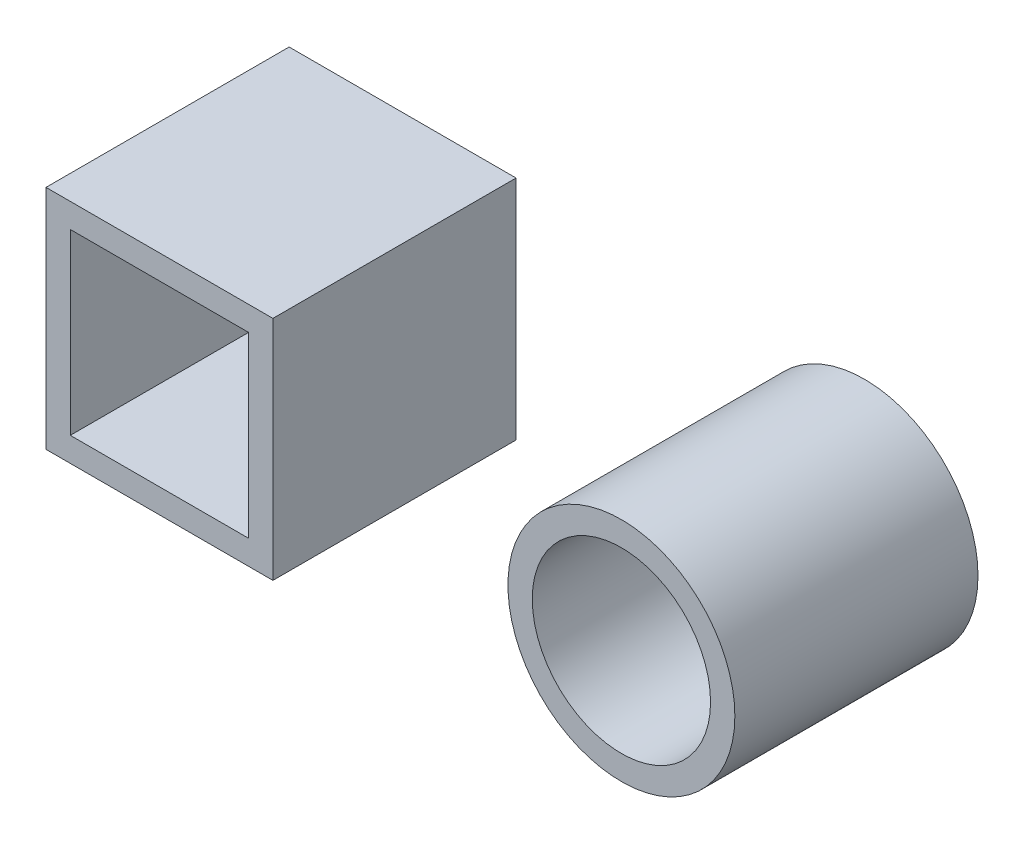
SolidWorks part; units mm, degrees
ref_plane "Front Plane" through (0, 0, 0) normal (0, 0, 1) x (1, 0, 0)
ref_plane "Top Plane" through (0, 0, 0) normal (0, 1, 0) x (1, 0, 0)
ref_plane "Right Plane" through (0, 0, 0) normal (1, 0, 0) x (0, 0, -1)
sketch "Sketch3" plane through (0, 0, 0) normal (0, 0, 1) x (1, 0, 0)
  line L0 (-122.5, 0) -> (122.5, 0) construction
  line L1 (-122.5, 60) -> (122.5, 60)
  line L2 (-122.5, 60) -> (-122.5, -60)
  line L3 (-122.5, -60) -> (122.5, -60)
  line L4 (122.5, 60) -> (122.5, -60)
  line L5 (0, 60) -> (0, -60) construction
  line L6 (-22.5, -12.9904) -> (0, 25.9808)
  line L7 (-92.5, 22.5) -> (-47.5, 22.5)
  line L8 (-92.5, 22.5) -> (-92.5, -22.5)
  line L9 (-92.5, -22.5) -> (-47.5, -22.5)
  line L10 (-47.5, 22.5) -> (-47.5, -22.5)
  line L11 (-92.5, 22.5) -> (-47.5, -22.5) construction
  line L12 (-92.5, -22.5) -> (-47.5, 22.5) construction
  line L14 (-1.3522, 0) -> (0, -1.3522)
  line L18 (0, 25.9808) -> (22.5, -12.9904)
  line L19 (22.5, -12.9904) -> (-22.5, -12.9904)
  line L20 (-22.5, -12.9904) -> (11.25, 6.4952) construction
  line L21 (22.5, -12.9904) -> (-11.25, 6.4952) construction
  line L22 (0, 25.9808) -> (0, 0) construction
  line L24 (-35, 35) -> (-105, 35)
  line L25 (-35, 35) -> (-35, -35)
  line L26 (-35, -35) -> (-105, -35)
  line L27 (-105, 35) -> (-105, -35)
  line L28 (-35, 35) -> (-105, -35) construction
  line L29 (-35, -35) -> (-105, 35) construction
  line L34 (-43.3297, 26.6703) -> (-96.6703, -26.6703) construction
  line L35 (-43.3297, -26.6703) -> (-96.6703, 26.6703) construction
  line L36 (-42.5, 27.5) -> (-97.5, 27.5)
  line L37 (-42.5, 27.5) -> (-42.5, -27.5)
  line L38 (-42.5, -27.5) -> (-97.5, -27.5)
  line L39 (-97.5, 27.5) -> (-97.5, -27.5)
  line L40 (-42.5, 27.5) -> (-97.5, -27.5) construction
  line L41 (-42.5, -27.5) -> (-97.5, 27.5) construction
  circle A0 centre (72.5, 0) radius 22.5
  circle A1 centre (72.5, 0) radius 35
  circle A2 centre (72.5, 0) radius 27.5
  point P4 (-70, 0)
  point P10 (-70, 0)
  point P20 (0, 0)
  point P27 (7.7505, -5.3087)
  point P28 (0, 0)
  point P32 (-70, 0)
  point P38 (-70, 0)
  dimension "D2" = 50
  dimension "D3" = 70
  dimension "cylinder" = 45
  dimension "D6" = 55
  dimension "D1" = 30
  dimension "D4" = 70
  dimension "square2" = 45
  dimension "D5" = 70
  dimension "square" = 45
  dimension "D7" = 55
  dimension "triangle3" = 45
  dimension "triangle2" = 45
  dimension "D8" = 55
  dimension "triangle" = 45
extrude "Boss-Extrude4" add sketch "Sketch3" against normal blind 75 contours L24 L27 L26 L25 L39 L36 L37 L38 | A1 A2
